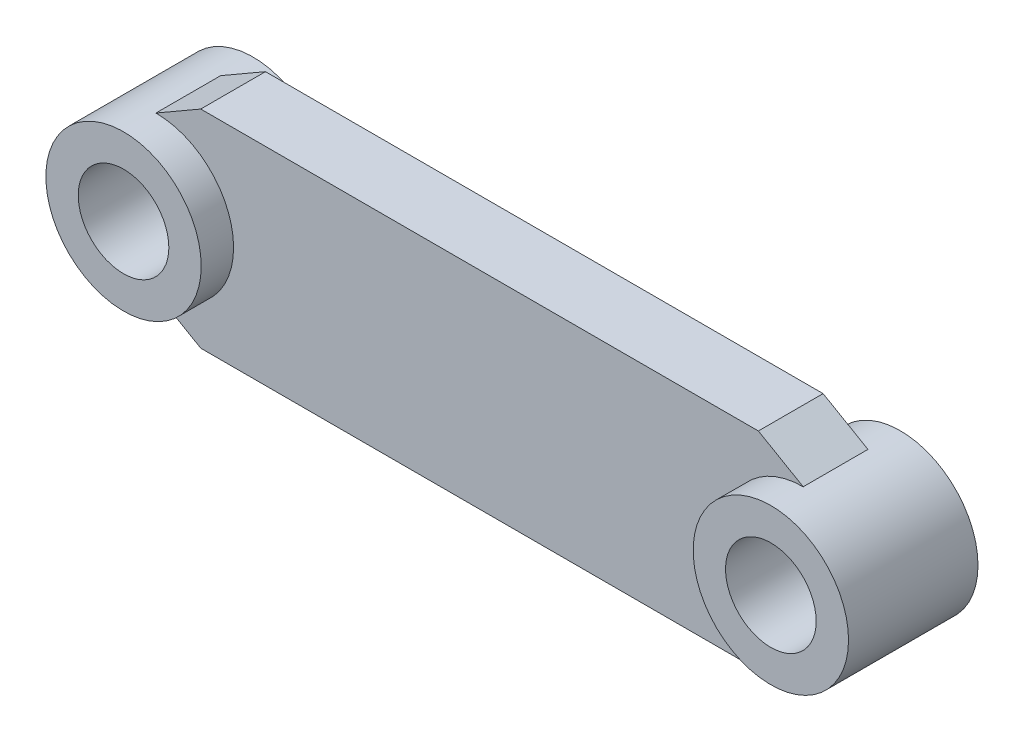
SolidWorks part; units mm, degrees
ref_plane "Front Plane" through (0, 0, 0) normal (0, 0, 1) x (1, 0, 0)
ref_plane "Top Plane" through (0, 0, 0) normal (0, 1, 0) x (1, 0, 0)
ref_plane "Right Plane" through (0, 0, 0) normal (1, 0, 0) x (0, 0, -1)
sketch "Sketch1" plane through (0, 0, 0) normal (0, 0, 1) x (1, 0, 0)
  line L0 (0, 6) -> (3.4641, 8)
  line L5 (0, 0) -> (50, 0) construction
  line L6 (25, 0) -> (25, 24.6492) construction
  line L7 (50, 6) -> (46.5359, 8)
  line L8 (46.5359, 8) -> (3.4641, 8)
  line L9 (0, -6) -> (3.4641, -8)
  line L10 (50, -6) -> (46.5359, -8)
  line L11 (46.5359, -8) -> (3.4641, -8)
  circle A4 centre (0, 0) radius 3.5
  circle A5 centre (0, 0) radius 6
  circle A6 centre (50, 0) radius 3.5
  circle A7 centre (50, 0) radius 6
  dimension "D2" = 12
  dimension "D3" = 50
  dimension "D4" = 30
  dimension "D5" = 30
  dimension "D1" = 7
  dimension "D6" = 8
extrude "Boss-Extrude1" add sketch "Sketch1" along normal mid plane 5 contours L10 A7 L7 L8 L0 A5 L9 L11 | A5 A4 | A7 A6
sketch "Sketch4" plane through (0, 0, 0) normal (0, 0, 1) x (1, 0, 0)
  circle A10 centre (0, 0) radius 6
  circle A11 centre (50, 0) radius 6
  circle A12 centre (50, 0) radius 3.5 construction
  circle A13 centre (0, 0) radius 3.5 construction
  circle A14 centre (50, 0) radius 3.5
  circle A15 centre (0, 0) radius 3.5
  arc A16 (0, 6) -> (0, -6) centre (0, 0) ccw construction
  arc A17 (50, -6) -> (50, 6) centre (50, 0) ccw construction
extrude "Boss-Extrude2" add sketch "Sketch4" along normal mid plane 10 contours A10 A15 | A11 A14
